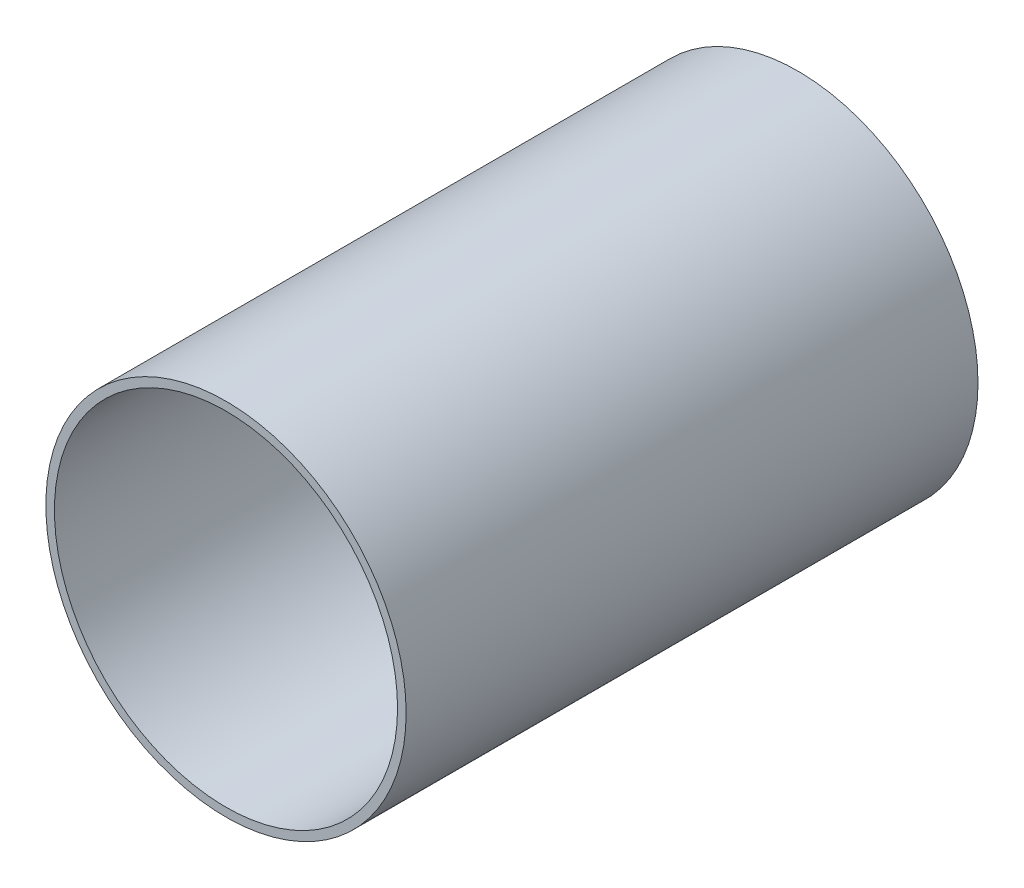
SolidWorks part; units mm, degrees
ref_plane "Plan de face" through (0, 0, 0) normal (0, 0, 1) x (1, 0, 0)
ref_plane "Plan de dessus" through (0, 0, 0) normal (0, 1, 0) x (1, 0, 0)
ref_plane "Plan de droite" through (0, 0, 0) normal (1, 0, 0) x (0, 0, -1)
sketch "Esquisse1" plane through (0, 0, 0) normal (0, 0, 1) x (1, 0, 0)
  circle A0 centre (0, 0) radius 30
  circle A1 centre (0, 0) radius 31.5
  dimension "D1" = 60
  dimension "D2" = 63
extrude "Boss.-Extru.1" add sketch "Esquisse1" along normal blind 100
